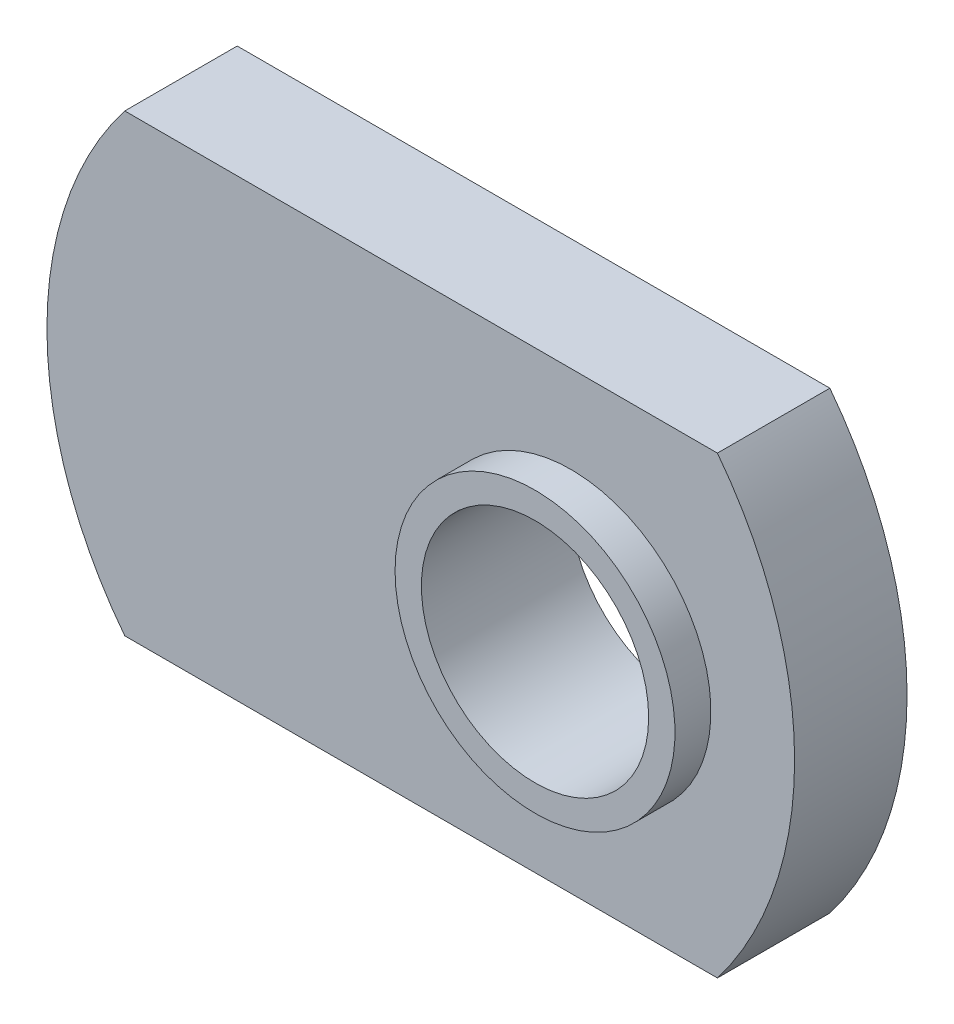
SolidWorks part; units mm, degrees
material "Chrome Stainless Steel"
ref_plane "Front Plane" through (0, 0, 0) normal (0, 0, 1) x (1, 0, 0)
ref_plane "Top Plane" through (0, 0, 0) normal (0, 1, 0) x (1, 0, 0)
ref_plane "Right Plane" through (0, 0, 0) normal (1, 0, 0) x (0, 0, -1)
sketch "Sketch1" plane through (0, 0, 0) normal (0, 0, 1) x (1, 0, 0)
  line L0 (-33.8495, 15.7042) -> (-17.9745, 15.7042) construction
  line L1 (-32.1972, 20.5302) -> (-19.6135, 20.5302)
  line L2 (-32.1972, 10.8782) -> (-19.6135, 10.8782)
  line L3 (-33.8495, 10.8782) -> (-17.9745, 10.8782) construction
  line L4 (-33.8495, 20.5302) -> (-17.9745, 20.5302) construction
  circle A0 centre (-22.7243, 15.7042) radius 2.413
  arc A1 (-19.6135, 10.8782) -> (-19.6135, 20.5302) centre (-25.8993, 15.7042) ccw
  arc A2 (-32.1972, 20.5302) -> (-32.1972, 10.8782) centre (-25.9755, 15.7042) ccw
  dimension "D2" = 4.826
  dimension "D1" = 15.875
  dimension "D3" = 4.826
extrude "Extrude1" add sketch "Sketch1" along normal blind 2.3876
sketch "Sketch2" plane through (0, 0, 2.3876) normal (0, 0, 1) x (1, 0, 0)
  circle A0 centre (-22.7243, 15.7042) radius 2.9718
  circle A1 centre (-22.7243, 15.7042) radius 2.413
extrude "Extrude2" add sketch "Sketch2" along normal blind 0.762
